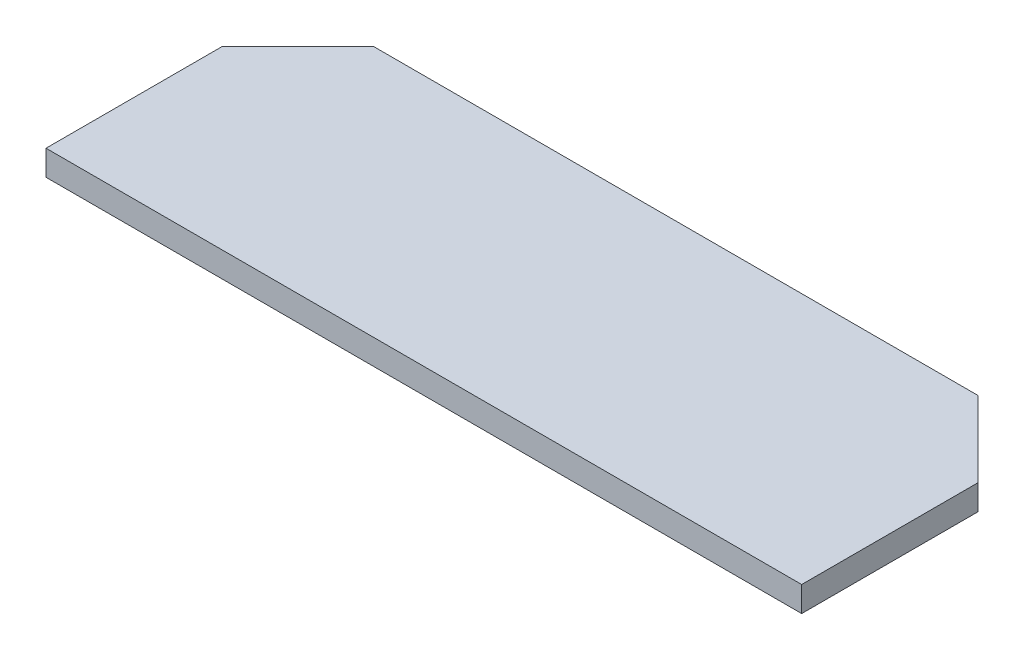
SolidWorks part; units mm, degrees
ref_plane "front" through (0, 0, 0) normal (0, 0, 1) x (1, 0, 0)
ref_plane "top" through (0, 0, 0) normal (0, 1, 0) x (1, 0, 0)
ref_plane "right" through (0, 0, 0) normal (1, 0, 0) x (0, 0, -1)
sketch "Sketch1" plane through (0, 0, 0) normal (0, 1, 0) x (1, 0, 0)
  line L0 (-76.2, 0) -> (76.2, 0)
  line L1 (76.2, 0) -> (95.25, -19.05)
  line L2 (95.25, -19.05) -> (95.25, -63.5)
  line L3 (95.25, -63.5) -> (-95.25, -63.5)
  line L4 (-95.25, -63.5) -> (-95.25, -19.05)
  line L5 (-95.25, -19.05) -> (-76.2, 0)
  line L6 (0, 0) -> (0, -28.5318) construction
  dimension "D1" = 19.05
  dimension "D2" = 19.05
  dimension "D3" = 190.5
  dimension "D4" = 63.5
extrude "Base-Extrude" add sketch "Sketch1" against normal blind 6.35
